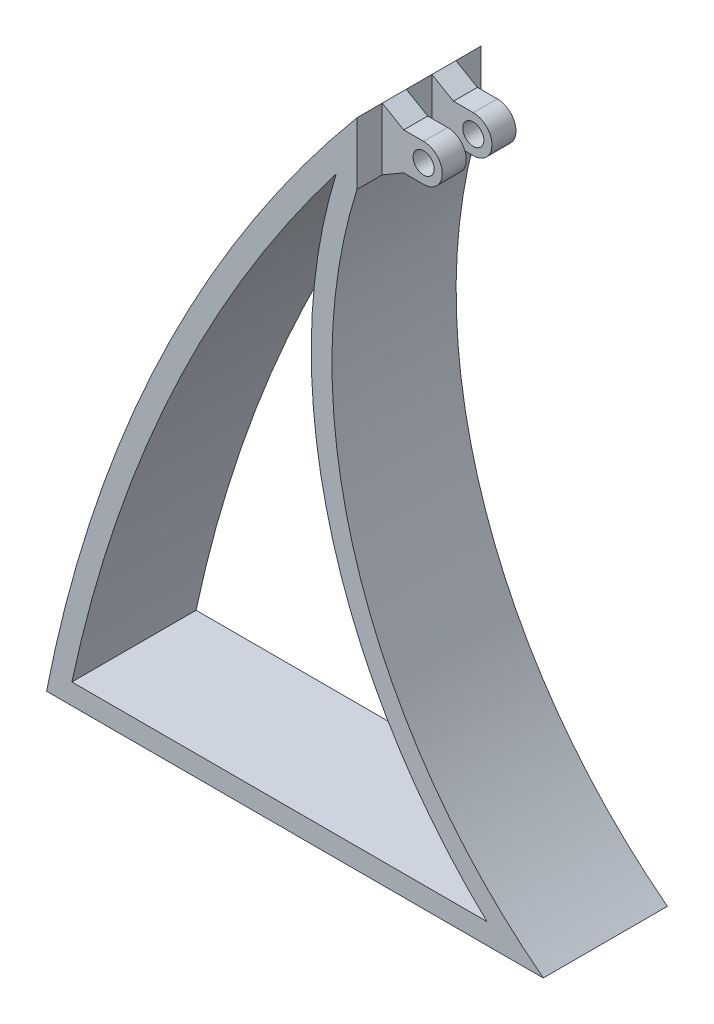
SolidWorks part; units mm, degrees
ref_plane "Front Plane" through (0, 0, 0) normal (0, 0, 1) x (1, 0, 0)
ref_plane "Top Plane" through (0, 0, 0) normal (0, 1, 0) x (1, 0, 0)
ref_plane "Right Plane" through (0, 0, 0) normal (1, 0, 0) x (0, 0, -1)
sketch "Sketch1" plane through (0, 0, 0) normal (0, 0, 1) x (1, 0, 0)
  line L0 (-60, 0) -> (60, 0)
  line L2 (15, 157.5) -> (15, 142.5)
  arc A2 (15, 157.5) -> (-60, 0) centre (283.5313, -66.9792) ccw
  arc A3 (15, 142.5) -> (60, 0) centre (138.9443, 103.285) ccw
  point P3 (61.5967, 0)
  point P8 (15, 150)
  dimension "D1" = 15
  dimension "D4" = 120
  dimension "D5" = 350
  dimension "D6" = 130
  dimension "D2" = 45
  dimension "D3" = 150
extrude "Boss-Extrude1" add sketch "Sketch1" along normal mid plane 30
sketch "Sketch3" plane through (0, 0, 15) normal (0, 0, 1) x (1, 0, 0)
  line L4 (10, 143.2647) -> (10, 143.2721)
  line L5 (-53.8764, 5) -> (46.3967, 5)
  line L6 (10, 143.2647) -> (10, 143.2721)
  line L7 (-53.8764, 5) -> (46.3967, 5)
  arc A4 (10, 143.2721) -> (-53.8764, 5) centre (283.5313, -66.9792) ccw
  arc A5 (10, 143.2647) -> (46.3967, 5) centre (138.9443, 103.285) ccw
  arc A6 (10, 143.2721) -> (-53.8764, 5) centre (283.5313, -66.9792) ccw
  arc A7 (10, 143.2647) -> (46.3967, 5) centre (138.9443, 103.285) ccw
  dimension "D1" = 5
extrude "Cut-Extrude1" cut sketch "Sketch3" against normal through all
sketch "Sketch4" plane through (0, 0, 0) normal (0, 0, 1) x (1, 0, 0)
  line L0 (25, 145.5) -> (20.1962, 145.5)
  line L2 (15, 157.5) -> (15, 142.5)
  line L7 (20.1962, 145.5) -> (15, 142.5)
  line L8 (25, 150) -> (40.3949, 150) construction
  line L9 (20.1962, 154.5) -> (15, 157.5)
  line L10 (25, 154.5) -> (20.1962, 154.5)
  circle A0 centre (25, 150) radius 2.55
  arc A1 (25, 154.5) -> (25, 145.5) centre (25, 150) cw
  point P7 (15, 150)
  dimension "D1" = 5.1
  dimension "D3" = 4.5
  dimension "D2" = 10
  dimension "D4" = 60
extrude "Boss-Extrude2" add sketch "Sketch4" along normal blind 5.8 from offset 3.1
mirror "Mirror1" about plane through (0, 0, 0) normal (0, 0, 1) of "Boss-Extrude2"
